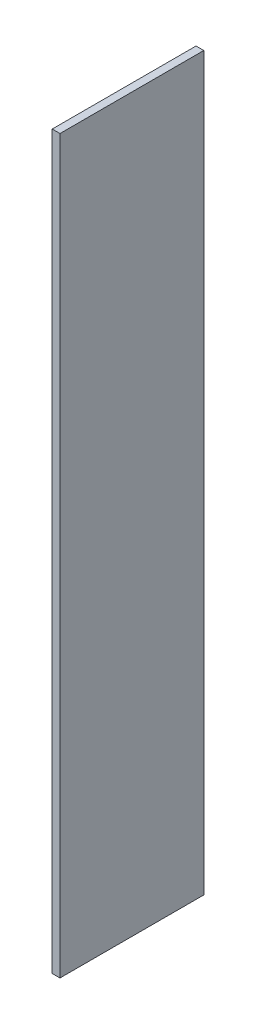
SolidWorks part; units mm, degrees
ref_plane "Front Plane" through (0, 0, 0) normal (0, 0, 1) x (1, 0, 0)
ref_plane "Top Plane" through (0, 0, 0) normal (0, 1, 0) x (1, 0, 0)
ref_plane "Right Plane" through (0, 0, 0) normal (1, 0, 0) x (0, 0, -1)
sketch "Sketch1" plane through (0, 0, 0) normal (1, 0, 0) x (0, 0, -1)
  line L1 (-28.2194, 143.51) -> (28.2194, 143.51)
  line L2 (-28.2194, 143.51) -> (-28.2194, -143.51)
  line L3 (-28.2194, -143.51) -> (28.2194, -143.51)
  line L4 (28.2194, 143.51) -> (28.2194, -143.51)
  line L5 (-28.2194, 143.51) -> (28.2194, -143.51) construction
  line L6 (-28.2194, -143.51) -> (28.2194, 143.51) construction
  point P0 (0, 0)
  dimension "D1" = 56.4388
  dimension "D2" = 287.02
extrude "Boss-Extrude1" add sketch "Sketch1" along normal blind 3.048
equation "\"motor offset\"=6mm"
equation "\"thickness0.25\"=0.225in"
equation "\"thickness0.125\"=0.122in"
equation "\"thickness_acrylic0.1\"= 0.1in"
equation "\"D1@Sketch1\"=\"thickness_acrylic0.1\"+\"thickness0.125\"+2"
